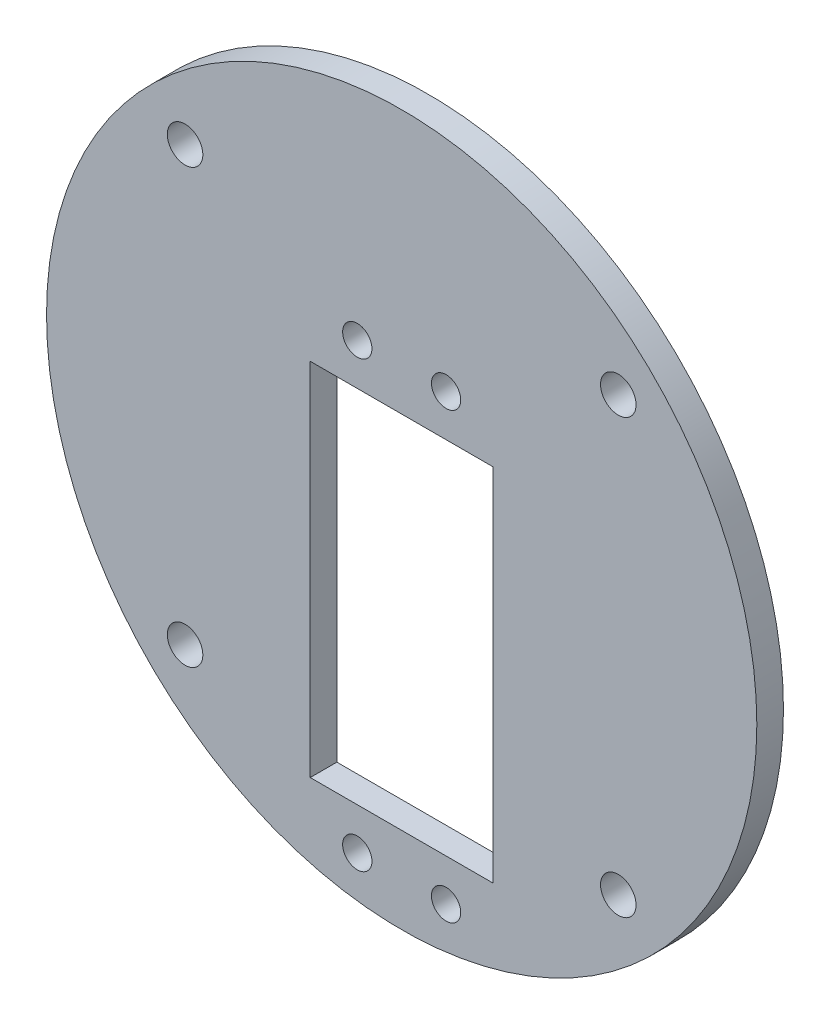
SolidWorks part; units mm, degrees
ref_plane "前视基准面" through (0, 0, 0) normal (0, 0, 1) x (1, 0, 0)
ref_plane "上视基准面" through (0, 0, 0) normal (0, 1, 0) x (1, 0, 0)
ref_plane "右视基准面" through (0, 0, 0) normal (1, 0, 0) x (0, 0, -1)
other "Configuration Table"
sketch "Plate_D80_Holes_D4_Diagonal69" plane through (0, 0, 0) normal (0, 0, 1) x (1, 0, 0)
  line L0 (-24.3952, -24.3952) -> (24.3952, 24.3952) construction
  circle A0 centre (0, 0) radius 40
  circle A1 centre (-24.3952, -24.3952) radius 2
  circle A2 centre (-24.3952, 24.3952) radius 2
  circle A3 centre (24.3952, -24.3952) radius 2
  circle A4 centre (24.3952, 24.3952) radius 2
  dimension "DiagonalPitch" = 69
extrude "Plate_3mm" add sketch "Plate_D80_Holes_D4_Diagonal69" along normal blind 3
sketch "Servo_Housing_Profile_40p6x20p6" plane through (0, 0, 0) normal (0, 0, 1) x (1, 0, 0)
  line L0 (-10.3, -30.3) -> (10.3, -30.3)
  line L1 (10.3, -30.3) -> (10.3, 10.3)
  line L2 (10.3, 10.3) -> (-10.3, 10.3)
  line L3 (-10.3, 10.3) -> (-10.3, -30.3)
extrude "Servo_Housing_Through_Cut" cut sketch "Servo_Housing_Profile_40p6x20p6" along normal blind 3.2 from offset 0.1
sketch "Servo_Ears_50x10_Centered_on_Shaft" plane through (0, 0, 0) normal (0, 0, 1) x (1, 0, 0)
  circle A0 centre (-5, -35) radius 1.65
  circle A1 centre (-5, 15) radius 1.65
  circle A2 centre (5, -35) radius 1.65
  circle A3 centre (5, 15) radius 1.65
extrude "Servo_4xD3p3_Through_Holes" cut sketch "Servo_Ears_50x10_Centered_on_Shaft" along normal blind 3.2 from offset 0.1
